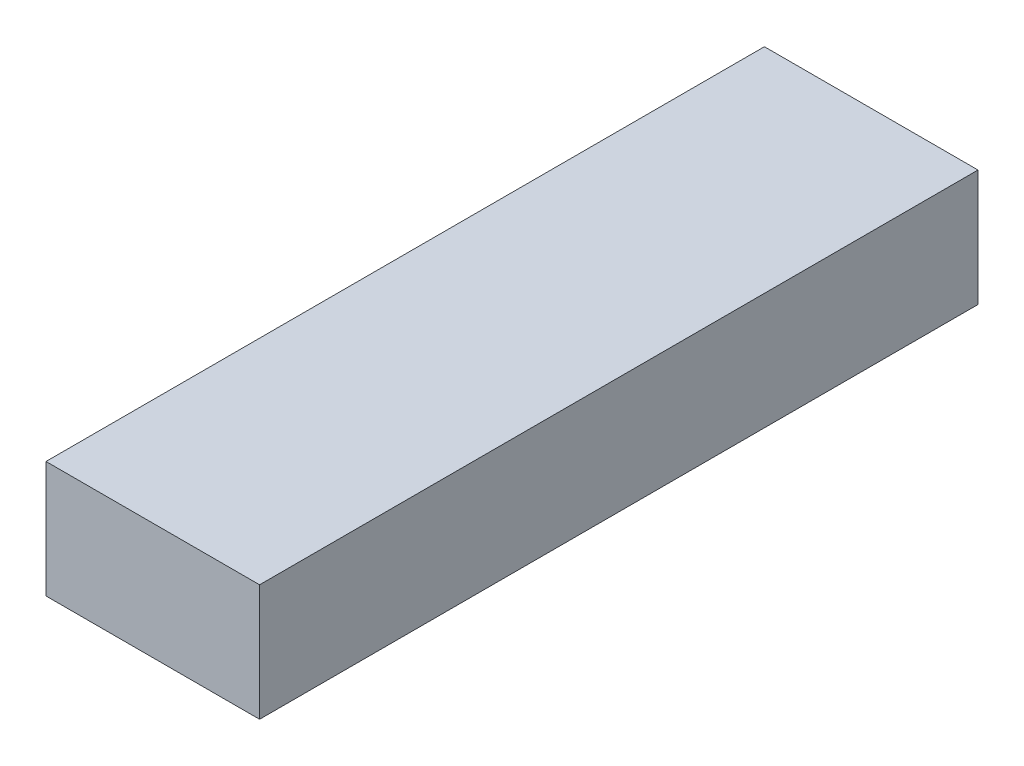
SolidWorks part; units mm, degrees
material "Pine"
ref_plane "Front Plane" through (0, 0, 0) normal (0, 0, 1) x (1, 0, 0)
ref_plane "Top Plane" through (0, 0, 0) normal (0, 1, 0) x (1, 0, 0)
ref_plane "Right Plane" through (0, 0, 0) normal (1, 0, 0) x (0, 0, -1)
sketch "Sketch2" plane through (0, 0, 0) normal (0, 1, 0) x (1, 0, 0)
  line L1 (-84.392, 129.2225) -> (-14.542, 129.2225)
  line L2 (-84.392, 129.2225) -> (-84.392, -105.7275)
  line L3 (-84.392, -105.7275) -> (-14.542, -105.7275)
  line L4 (-14.542, 129.2225) -> (-14.542, -105.7275)
  point P4 (0, 0)
  dimension "D1" = 234.95
  dimension "D2" = 69.85
extrude "Boss-Extrude1" add sketch "Sketch2" along normal blind 38.1
